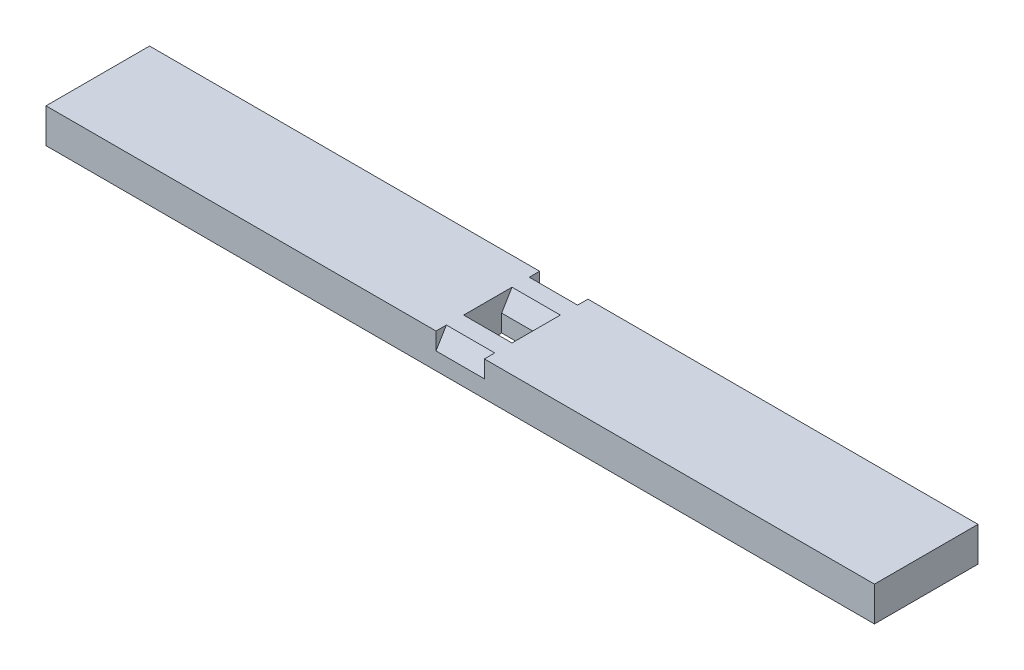
SolidWorks part; units mm, degrees
ref_plane "Front Plane" through (0, 0, 0) normal (0, 0, 1) x (1, 0, 0)
ref_plane "Top Plane" through (0, 0, 0) normal (0, 1, 0) x (1, 0, 0)
ref_plane "Right Plane" through (0, 0, 0) normal (1, 0, 0) x (0, 0, -1)
sketch "Sketch1" plane through (0, 0, 0) normal (0, 1, 0) x (1, 0, 0)
  line L1 (0, 0) -> (120, 0)
  line L2 (0, 0) -> (0, 15)
  line L3 (0, 15) -> (120, 15)
  line L4 (120, 0) -> (120, 15)
  dimension "D1" = 15
  dimension "D2" = 120
extrude "Boss-Extrude1" add sketch "Sketch1" along normal blind 5
sketch "Sketch2" plane through (0, 5, 0) normal (0, 1, 0) x (1, 0, 0)
  line L0 (60, 15) -> (60, 0) construction
  line L1 (120, 15) -> (0, 15) construction
  line L2 (0, 0) -> (120, 0) construction
  line L4 (56.5, 5.5) -> (63.5, 5.5)
  line L5 (56.5, 5.5) -> (56.5, 9.5)
  line L6 (56.5, 9.5) -> (63.5, 9.5)
  line L7 (63.5, 5.5) -> (63.5, 9.5)
  line L8 (56.5, 5.5) -> (63.5, 9.5) construction
  line L9 (56.5, 9.5) -> (63.5, 5.5) construction
  point P6 (60, 7.5)
  dimension "D1" = 4
  dimension "D2" = 7
extrude "Cut-Extrude1" cut sketch "Sketch2" against normal blind 10
sketch "Sketch3" plane through (56.5, 0, 0) normal (1, 0, 0) x (0, 0, -1)
  line L0 (5.5, 5) -> (3.9979, 5)
  line L1 (15, 5) -> (0, 5) construction
  line L2 (3.9979, 5) -> (5.5, 2.5)
  line L3 (5.5, 0) -> (5.5, 5) construction
  line L4 (5.5, 2.5) -> (5.5, 5)
  line L5 (9.5, 5) -> (11, 5)
  line L6 (11, 5) -> (9.5, 2.5)
  line L7 (9.5, 0) -> (9.5, 5) construction
  line L8 (9.5, 2.5) -> (9.5, 5)
  line L9 (1.5, 5) -> (0, 2.5)
  line L10 (0, 5) -> (0, 0) construction
  line L11 (0, 2.5) -> (0, 5)
  line L12 (0, 5) -> (1.5, 5)
  line L13 (13.5, 5) -> (15, 2.5)
  line L14 (15, 5) -> (15, 0) construction
  line L15 (15, 2.5) -> (15, 5)
  line L16 (15, 5) -> (13.5, 5)
  dimension "D1" = 1.5021
  dimension "D2" = 1.5
  dimension "D3" = 1.5
  dimension "D4" = 1.5
extrude "Cut-Extrude2" cut sketch "Sketch3" along normal up to surface (7 mm away) up to face at (63.5, 2.5, -7.5)
